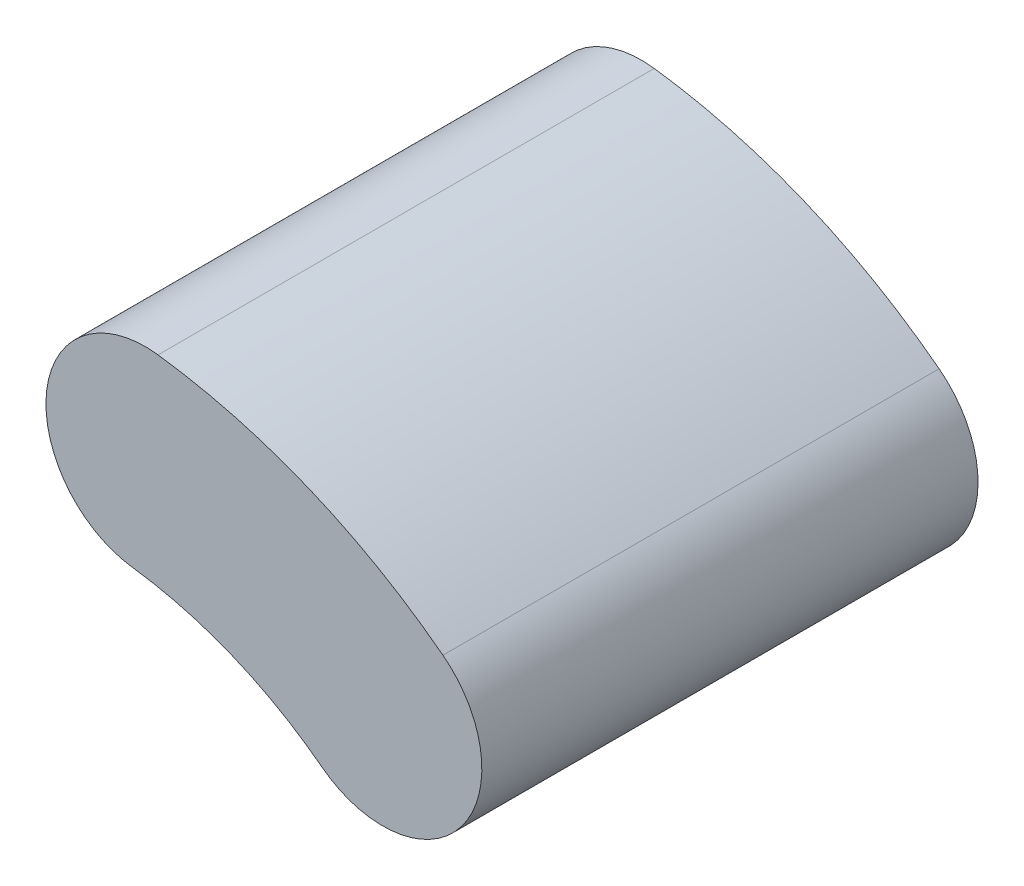
SolidWorks part; units mm, degrees
ref_plane "Front Plane" through (0, 0, 0) normal (0, 0, 1) x (1, 0, 0)
ref_plane "Top Plane" through (0, 0, 0) normal (0, 1, 0) x (1, 0, 0)
ref_plane "Right Plane" through (0, 0, 0) normal (1, 0, 0) x (0, 0, -1)
other "Configuration Table"
sketch "Sketch1" plane through (0, 0, 0) normal (0, 0, 1) x (1, 0, 0)
  arc A0 (60.79, 79.4014) -> (12.945, 99.1586) centre (0, 0) ccw construction
  arc A1 (72.948, 95.2816) -> (15.534, 118.9903) centre (0, 0) ccw
  arc A2 (48.632, 63.5211) -> (10.356, 79.3269) centre (0, 0) ccw
  arc A3 (48.632, 63.5211) -> (72.948, 95.2816) centre (60.79, 79.4014) ccw
  arc A4 (15.534, 118.9903) -> (10.356, 79.3269) centre (12.945, 99.1586) ccw
  point P3 (38.168, 92.4294)
  dimension "D3" = 100
  dimension "D1" = 40
  dimension "D2" = 30
extrude "Boss-Extrude1" add sketch "Sketch1" along normal blind 100
